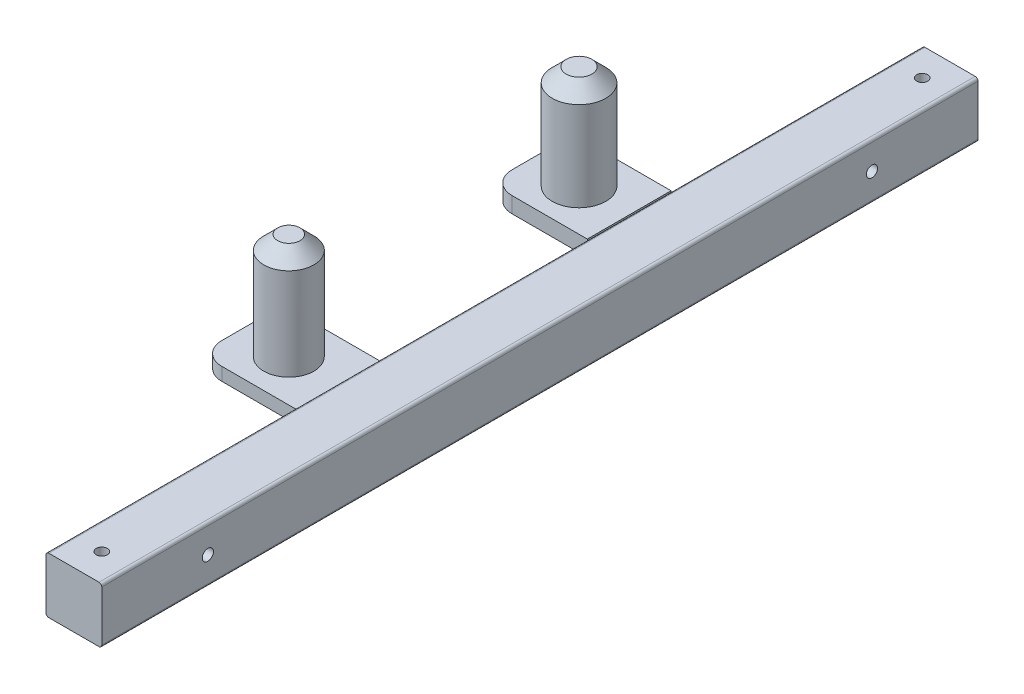
SolidWorks part; units mm, degrees
ref_plane "前视基准面" through (0, 0, 0) normal (0, 0, 1) x (1, 0, 0)
ref_plane "上视基准面" through (0, 0, 0) normal (0, 1, 0) x (1, 0, 0)
ref_plane "右视基准面" through (0, 0, 0) normal (1, 0, 0) x (0, 0, -1)
sketch "草图1" plane through (0, 0, 0) normal (0, 0, 1) x (1, 0, 0)
  line L1 (0, 0) -> (20, 0)
  line L2 (0, 0) -> (0, 20)
  line L3 (0, 20) -> (20, 20)
  line L4 (20, 0) -> (20, 20)
  dimension "D1" = 20
  dimension "D2" = 20
extrude "凸台-拉伸1" add sketch "草图1" along normal blind 314
sketch "草图2" plane through (0, 20, 0) normal (0, 1, 0) x (1, 0, 0)
  line L0 (20, 0) -> (0, 0) construction
  line L1 (20, -314) -> (0, -314) construction
  circle A0 centre (10, -10) radius 2
  circle A1 centre (10, -304) radius 2
  point P8 (10, 0)
  dimension "D3" = 4
  dimension "D1" = 10
  dimension "D2" = 10
extrude "切除-拉伸1" cut sketch "草图2" against normal blind 314
fillet "圆角1" radius 1 4 edges at (0, 0, 157) (20, 0, 157) (0, 20, 157) (20, 20, 157)
sketch "草图3" plane through (0, 0, 0) normal (-1, 0, 0) x (0, 0, 1)
  line L0 (0, 19) -> (0, 1) construction
  line L1 (314, 19) -> (314, 1) construction
  circle A0 centre (276, 10) radius 2
  circle A1 centre (38, 10) radius 2
  point P8 (0, 10)
  dimension "D3" = 4
  dimension "D1" = 38
  dimension "D2" = 38
extrude "切除-拉伸2" cut sketch "草图3" against normal blind 20
sketch "草图4" plane through (0, 0, 0) normal (-1, 0, 0) x (0, 0, 1)
  line L0 (0, 20) -> (314, 20) construction
  line L1 (90, 20) -> (120, 20)
  line L2 (90, 20) -> (90, 14.3386)
  line L3 (90, 14.3386) -> (120, 14.3386)
  line L4 (120, 20) -> (120, 14.3386)
  line L5 (314, 19) -> (0, 19) construction
  line L6 (224, 19) -> (194, 19)
  line L7 (224, 19) -> (224, 14.3386)
  line L8 (224, 14.3386) -> (194, 14.3386)
  line L9 (194, 19) -> (194, 14.3386)
  line L10 (314, 19) -> (314, 1) construction
  dimension "D1" = 30
  dimension "D2" = 30
  dimension "D3" = 120
  dimension "D4" = 120
extrude "凸台-拉伸2" add sketch "草图4" along normal blind 35
sketch "草图5" plane through (0, 19, 0) normal (0, 1, 0) x (1, 0, 0)
  circle A0 centre (-17.9783, -209) radius 8.9932
  circle A1 centre (-17.9783, -105) radius 9.5979
  dimension "D1" = 104
extrude "凸台-拉伸3" add sketch "草图5" along normal blind 38
fillet "圆角2" radius 8 4 edges at (-35, 17.1693, 90) (-35, 17.1693, 120) (-35, 16.6693, 194) (-35, 16.6693, 224)
chamfer "倒角1" distance 5 angle 45 2 edges at (-17.9783, 57, 114.5979) (-17.9783, 57, 217.9932)
